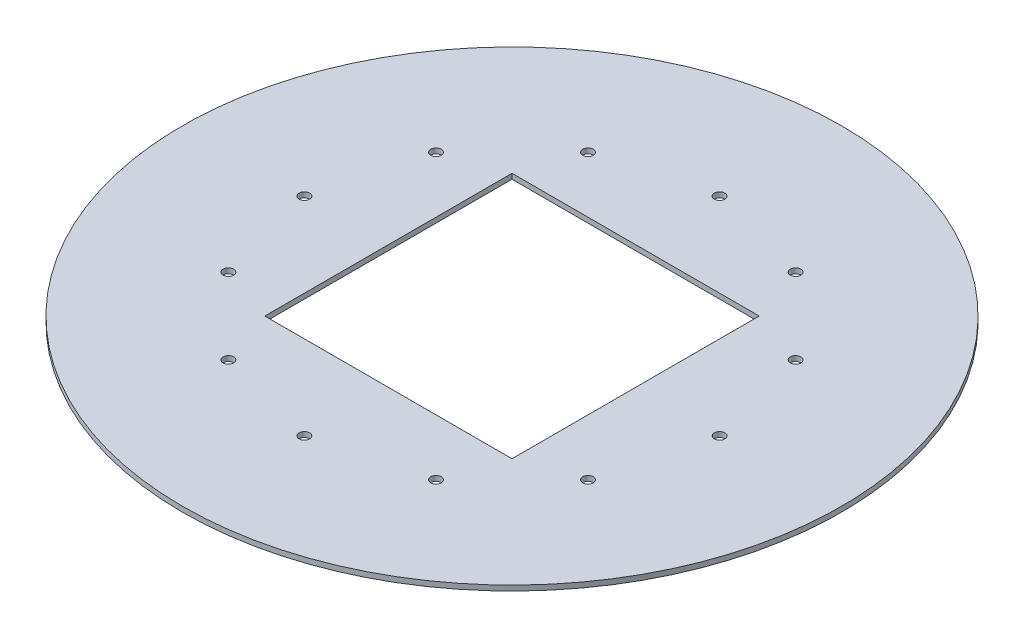
SolidWorks part; units mm, degrees
material "Thornel VCB-20 Carbon Cloth"
ref_plane "Front Plane" through (0, 0, 0) normal (0, 0, 1) x (1, 0, 0)
ref_plane "Top Plane" through (0, 0, 0) normal (0, 1, 0) x (1, 0, 0)
ref_plane "Right Plane" through (0, 0, 0) normal (1, 0, 0) x (0, 0, -1)
sketch "Sketch1" plane through (0, 0, 0) normal (0, 0, 1) x (1, 0, 0)
  line L0 (-60, -0.785) -> (-100, -0.785) construction
  line L1 (-60, 0.785) -> (-60, -0.785) construction
  line L2 (-60, 0.785) -> (-100, 0.785) construction
  line L3 (-100, 0.785) -> (-100, -0.785) construction
  line L4 (-60, -0.785) -> (-100, -0.785)
  line L5 (-60, 0.785) -> (-60, -0.785)
  line L6 (-60, 0.785) -> (-100, 0.785)
  line L7 (-100, 0.785) -> (-100, -0.785)
  line L8 (0, -200069.0475) -> (0, 200086.9028) construction
  line L9 (0, -200069.0475) -> (0, 200086.9028) construction
revolve "Revolve1" add sketch "Sketch1" angle 360 about L9
sketch "Sketch2" plane through (0, 0.785, 0) normal (0, 1, 0) x (1, 0, 0)
  line L1 (-37.5, -37.5) -> (37.5, -37.5)
  line L2 (-37.5, -37.5) -> (-37.5, 37.5)
  line L3 (-37.5, 37.5) -> (37.5, 37.5)
  line L4 (37.5, -37.5) -> (37.5, 37.5)
  line L5 (-37.5, -37.5) -> (37.5, 37.5) construction
  line L6 (-37.5, 37.5) -> (37.5, -37.5) construction
  circle A0 centre (0, 0) radius 60 construction
  circle A1 centre (0, 0) radius 60
  dimension "D1" = 75
  dimension "D2" = 75
extrude "Boss-Extrude1" add sketch "Sketch2" against normal up to surface (1.57 mm away) up to face at (0, -0.785, -60)
sketch "Sketch3" plane through (0, 0.785, 0) normal (0, 1, 0) x (1, 0, 0)
  circle A1 centre (0, 63) radius 1.6
  circle A2 centre (0, 63) radius 1.6
  dimension "D1" = 0
extrude "Cut-Extrude1" cut sketch "Sketch3" against normal through all
pattern_circular "CirPattern1" count 12 over 360 about axis through (0, 0, 0) along (0, 1, 0) of "Cut-Extrude1"
